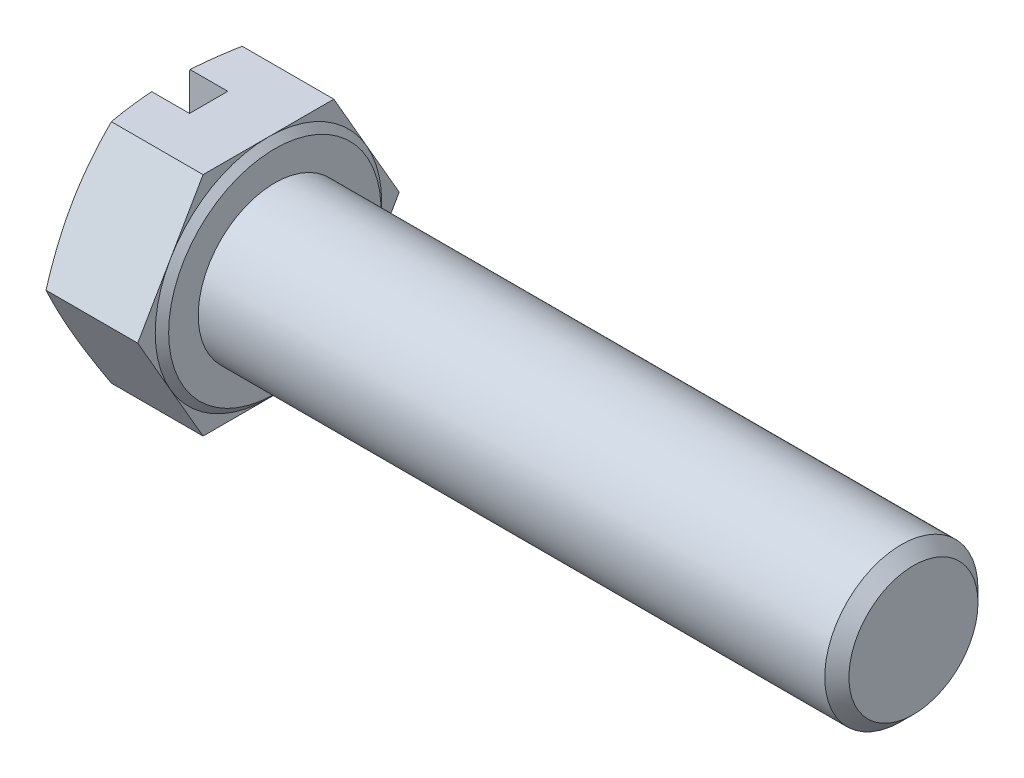
SolidWorks part; units mm, degrees
ref_plane "Front" through (0, 0, 0) normal (0, 0, 1) x (1, 0, 0)
ref_plane "Top" through (0, 0, 0) normal (0, 1, 0) x (1, 0, 0)
ref_plane "Right" through (0, 0, 0) normal (1, 0, 0) x (0, 0, -1)
sketch "Sketch-BaseHead" plane through (0, 0, 0) normal (1, 0, 0) x (0, 0, -1)
  line L1 (5.1182, -8.865) -> (10.2364, 0)
  line L2 (10.2364, 0) -> (5.1182, 8.865)
  line L3 (5.1182, 8.865) -> (-5.1182, 8.865)
  line L4 (-5.1182, 8.865) -> (-10.2364, 0)
  line L5 (-10.2364, 0) -> (-5.1182, -8.865)
  line L6 (-5.1182, -8.865) -> (5.1182, -8.865)
  circle A0 centre (0, 0) radius 8.865 construction
  dimension "s" = 17.73
extrude "BaseHead" add sketch "Sketch-BaseHead" along normal blind 7.68
ref_plane "Plane1" through (8.28, 0, 0) normal (1, 0, 0) x (0, 0, -1)
sketch "Sketch1" plane through (0, 0, 0) normal (0, 0, 1) x (1, 0, 0)
  line L0 (7.68, 0) -> (8.18, 0)
  line L1 (8.18, 0) -> (8.18, -8.315)
  line L2 (8.18, -8.315) -> (7.68, -8.865)
  line L3 (7.68, -8.865) -> (7.68, 0)
  dimension "D1" = 8.865
  dimension "D2" = 0.5
  dimension "D3" = 8.315
revolve "Revolve1" add sketch "Sketch1" angle 360 about axis through (-4.0016, 0, 0) along (1, 0, 0)
sketch "Sketch3" plane through (8.18, 0, 0) normal (1, 0, 0) x (0, 0, -1)
  circle A0 centre (0, 0) radius 6
  dimension "d" = 12
extrude "BaseBody" add sketch "Sketch3" along normal blind 50
cosmetic thread "ThreadCosmetic1" [suppressed] parameters "D2"=10.106
chamfer "Chamfer1" distance 0.947 angle 45 1 edges at (58.18, 0, -6)
fillet "HeadFillet" [suppressed] radius 0.6
sketch "Sketch4" plane through (-0.2646, 0, 5.9169) normal (0, 1, 0) x (0, 0, -1)
  line L0 (5.9169, 3.7369) -> (5.9169, -10.4477) construction
  line L2 (16.1533, -0.2646) -> (14.7819, -0.2646)
  line L4 (14.7819, -0.2646) -> (16.1533, -0.7638)
  line L6 (16.1533, -0.7638) -> (16.1533, -0.2646)
  dimension "D1" = 20
  dimension "D2" = 17.73
revolve "HeadChamfer" cut sketch "Sketch4" angle 360 about L0
sketch "Sketch5" plane through (0, 0, 0) normal (0, 1, 0) x (1, 0, 0)
  line L0 (0, 1.5) -> (0, -1.5)
  line L1 (3, -1.5) -> (3, 1.5)
  line L2 (3, 1.5) -> (0, 1.5)
  line L3 (0, -1.5) -> (3, -1.5)
  dimension "n" = 3
  dimension "t" = 3
extrude "Slot" cut sketch "Sketch5" against normal through all and the other way through all
sketch "Sketch6" plane through (0, 0, 0) normal (0, 0, 1) x (1, 0, 0)
  line L0 (8.18, 6.2) -> (9.127, 6.2)
  line L1 (9.127, 6.2) -> (9.127, 6)
  line L2 (9.127, 6) -> (8.6535, 5.1799)
  line L3 (8.18, 6) -> (8.6535, 5.1799)
  line L4 (8.18, 6.2) -> (8.18, 6)
  line L5 (14.0487, 0) -> (0, 0) construction
  line L6 (8.18, 6) -> (9.127, 6) construction
  line L7 (8.6535, 6) -> (8.6535, 5.1799) construction
  point P5 (8.6535, 6.2)
  dimension "D1" = 0.2
  dimension "D2" = 0.947
revolve "Cut-Revolve10" [suppressed] cut sketch "Sketch6" angle 360 about L5
pattern_linear "LPattern10" [suppressed] count 44 spacing 1.1364
equation "\"D1@Sketch1\" = \"s@Sketch-BaseHead\"/ 2 "
equation "\"D2@Sketch4\" = \"s@Sketch-BaseHead\""
equation "\"D1@Chamfer1\" =  ( \"d@Sketch3\" - \"D2@ThreadCosmetic1\" ) / 2 "
equation "\"D2@Sketch6\" = (  \"d@Sketch3\" - \"D2@ThreadCosmetic1\" )  / 2"
equation "\"D3@LPattern10\" = \"D2@Sketch6\" * 1.2"
equation "\"D1@LPattern10\" = \"l@BaseBody\" / \"D3@LPattern10\""
